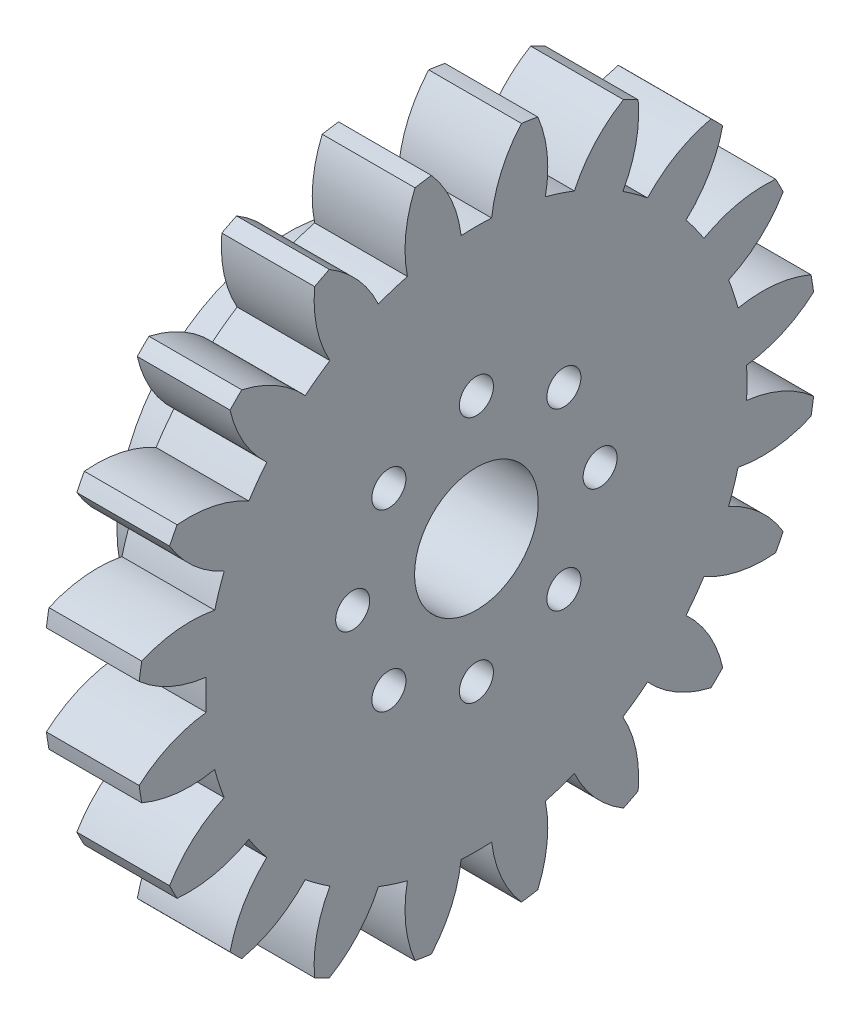
SolidWorks part; units mm, degrees
ref_plane "Plane1" through (0, 0, 0) normal (0, 0, 1) x (1, 0, 0)
ref_plane "Plane2" through (0, 0, 0) normal (0, 1, 0) x (1, 0, 0)
ref_plane "Plane3" through (0, 0, 0) normal (1, 0, 0) x (0, 0, -1)
other "Configuration Table"
sketch "HoldingSke" plane through (0, 0, 0) normal (0, 1, 0) x (1, 0, 0)
  line L0 (0, 0) -> (0.4698, -0.171)
  line L1 (-15, 0) -> (100, 0) construction
  line L2 (0, 0) -> (-2.1039, 2.3779)
  line L3 (0, 0) -> (-11.863, 4.5341)
  line L4 (0, 0) -> (8.1152, 2.9537)
  line L5 (0, 0) -> (-11.4777, -4.2808)
  line L6 (0, 0) -> (-4.9738, -3.3558)
  line L7 (-2.1039, 2.3779) -> (0.5329, 14.3408)
  line L8 (-76.2, 54.61) -> (-74.8, 54.61)
  line L9 (-71.009, 38.7566) -> (-53.1078, 45.2721)
  line L10 (-76.2, 71.12) -> (104.1128, 71.12)
  line L11 (0, 0) -> (-6, 0)
  line L12 (-76.2, 101.6) -> (-76.133, 101.6)
  line L13 (24.9733, 27.94) -> (52.9518, 28.4284)
  line L14 (24.9733, 27.94) -> (24.9743, 27.94)
  line L15 (24.9733, 27.94) -> (100.4006, 29.5858)
  line L16 (-63.627, -2) -> (-12.827, -2)
  circle A0 centre (0, 0) radius 4
  circle A1 centre (0, 0) radius 11
  circle A2 centre (0, 0) radius 11
  circle A3 centre (0, 0) radius 4
  dimension "MHD" = 22
  dimension "Hub_dia" = 22
  dimension "Bore" = 8
  dimension "MBD" = 8
  dimension "Num_teeth" = 20
  dimension "Pitch" = 0.5
  dimension "Overall_len" = 12.25
  dimension "Show_teeth" = 20
  dimension "Thickness" = 6
  dimension "OAL" = 12.2501
  dimension "T_dim" = 1.4
  dimension "Ap" = 20
  dimension "H" = 19.05
  dimension "Pitch_radius" = 180.3128
  dimension "Width" = 6
  dimension "Backlash" = 0.067
  dimension "Addendum_fac" = 1
  dimension "Dedendum_fac" = 1.25
  dimension "Clearance_fac" = 0.25
  dimension "Dedendum_add" = 0.001
  dimension "Module" = 2
sketch "BasProSke" plane through (0, 0, 0) normal (0, 1, 0) x (1, 0, 0)
  line L0 (-10, 0) -> (60, 0) construction
  line L1 (0, 0) -> (0, 22)
  line L2 (0, 0) -> (6, 0)
  line L3 (6, 0) -> (6, 22)
  line L4 (6, 22) -> (0, 22)
  dimension "Thickness" = 6
  dimension "Diameter" = 44
revolve "Base-Revolve" add sketch "BasProSke" angle 360 about L0
sketch "TooCutSke" plane through (0, 0, 0) normal (1, 0, 0) x (0, 0, -1)
  line L1 (0, 0) -> (0, 107) construction
  line L2 (0, 0) -> (-1.6864, 19.9288) construction
  line L3 (0, 0) -> (-6.2409, 39.4033) construction
  line L4 (-1.6864, 19.9288) -> (-3.1204, 19.7016) construction
  arc A0 (0.9862, 17.4712) -> (-0.9862, 17.4712) centre (0, 0) ccw
  arc A1 (2.9329, 21.8293) -> (-2.9329, 21.8293) centre (0, 0) ccw
  circle A2 centre (0, 0) radius 20 construction
  circle A3 centre (0, 0) radius 18.7939 construction
  arc A4 (-0.9862, 17.4712) -> (-2.9329, 21.8293) centre (-8.9313, 16.536) ccw
  arc A5 (2.9329, 21.8293) -> (0.9862, 17.4712) centre (8.9313, 16.536) ccw
  dimension "Root_dia" = 34.998
  dimension "Overcut_dia" = 44.0508
  dimension "Pitch_dia" = 40
  dimension "Base_dia" = 37.5877
  dimension "Flank_rad" = 8
  dimension "Half_ang" = 9
  dimension "Half_CT" = 1.4519
extrude "ToothCut" cut sketch "TooCutSke" along normal through all
fillet "Breaks" [suppressed] radius 0.04
fillet "RootFillets" [suppressed] radius 0.501
pattern_circular "TeethCuts" count 20 every 18 about axis through (-10, 0, 0) along (1, 0, 0) of "ToothCut", "RootFillets", "Breaks"
sketch "HubNeaOneSke" plane through (0, 0, 0) normal (-1, 0, 0) x (0, 0, 1)
  circle A0 centre (0, 0) radius 11
  dimension "Diameter" = 22
extrude "HubNearOne" add sketch "HubNeaOneSke" along normal blind 6.2501
sketch "HubNeaBotSke" plane through (0, 0, 0) normal (-1, 0, 0) x (0, 0, 1)
  circle A0 centre (0, 0) radius 11
  dimension "Diameter" = 22
extrude "HubNearBoth" [suppressed] add sketch "HubNeaBotSke" along normal blind 3.125
ref_plane "FarPln" through (6, 0, 0) normal (1, 0, 0) x (0, 0, -1)
sketch "HubFarSke" plane through (6, 0, 0) normal (1, 0, 0) x (0, 0, -1)
  circle A0 centre (0, 0) radius 11
  dimension "Diameter" = 22
extrude "HubFar" [suppressed] add sketch "HubFarSke" along normal blind 3.125
sketch "BorSke" plane through (0, 0, 0) normal (1, 0, 0) x (0, 0, -1)
  circle A0 centre (0, 0) radius 4
  dimension "Diameter" = 8
extrude "Bore" cut sketch "BorSke" along normal mid plane 24.5001
sketch "KeySke" plane through (0, 0, 0) normal (1, 0, 0) x (0, 0, -1)
  line L0 (-1.5, 0) -> (-1.5, 5.4)
  line L1 (-1.5, 5.4) -> (1.5, 5.4)
  line L2 (1.5, 5.4) -> (1.5, 0)
  line L3 (0, 0) -> (0, 34) construction
  line L4 (-1.5, 0) -> (1.5, 0)
  dimension "Offset" = 5.4
  dimension "Width" = 3
extrude "Keyway" [suppressed] cut sketch "KeySke" along normal mid plane 24.5001
pattern_circular "Keyway2" [suppressed] count 2 every 90 about axis through (-10, 0, 0) along (1, 0, 0)
hole_wizard "M2 Clearance Hole1" positions "Sketch1" profile "Sketch2" hole size "M2" standard "ANSI Metric" end condition through all
sketch "Sketch1" plane through (6, 0, 0) normal (1, 0, 0) x (0, 0, -1)
  circle A0 centre (0, 0) radius 8
  circle A1 centre (0, 0) radius 8
  circle A2 centre (0, 0) radius 8
  circle A3 centre (0, 0) radius 8
  circle A4 centre (0, 0) radius 8
  circle A5 centre (0, 0) radius 8
  circle A6 centre (0, 0) radius 8
  circle A7 centre (0, 0) radius 8
  point P2 (0, 8)
  point P23 (0, 8)
  point P32 (5.6569, 5.6569)
  point P34 (8, 0)
  point P36 (5.6569, -5.6569)
  point P38 (0, -8)
  point P40 (-5.6569, -5.6569)
  point P42 (-8, 0)
  point P44 (-5.6569, 5.6569)
  dimension "D1" = 16
  dimension "D2" = 8
sketch "Sketch2" plane through (6, 8, 0) normal (0, 1, 0) x (0, 0, -1)
  line L0 (0, 0) -> (0, 12.2501)
  line L1 (0, 12.2501) -> (1.1, 12.2501)
  line L2 (1.1, 12.2501) -> (1.1, 0)
  line L5 (1.1, 0) -> (0, 0)
  line L11 (0, -6.35) -> (0, 107.95) construction
  dimension "Thru Hole Dia." = 2.2
  dimension "Thru Hole Depth" = 12.2501
equation "' \"Module@HoldingSke\" = 6.35"
equation "' \"Num_teeth@HoldingSke\" = 12"
equation "' \"Ap@HoldingSke\" =  20"
equation "' \"Ap@HoldingSke\" = 20"
equation "' \"Width@HoldingSke\" = 0.5 * 25.4"
equation "' \"Hub_dia@HoldingSke\"= 1 * 25.4"
equation "' \"Hub_dia@HoldingSke\" = 1 * 25.4"
equation "' \"Overall_len@HoldingSke\" = 1.0 * 25.4"
equation "' \"Bore@HoldingSke\" = 0.75 * 25.4"
equation "' \"T_dim@HoldingSke\" = 0.1 * 25.4"
equation "' \"Width@KeySke\" = 0.25 * 25.4"
equation "' \"Show_teeth@HoldingSke\" = 13"
equation "' \"Backlash@HoldingSke\" = 0.009 * 25.4"
equation "' \"Addendum_fac@HoldingSke\" = 1.0"
equation "' \"Dedendum_fac@HoldingSke\" = 1.25"
equation "' \"Dedendum_add@HoldingSke\" = 0.00005 * 25.4"
equation "' \"Clearance_fac@HoldingSke\" = 0.25"
equation "\"Pitch@HoldingSke\" = 1 / \"Module@HoldingSke\""
equation "\"Overcut_dia@TooCutSke\" = (\"Num_teeth@HoldingSke\" + 2 * \"Addendum_fac@HoldingSke\") / \"Pitch@HoldingSke\" + 0.002 * 25.4"
equation "\"Pitch_dia@TooCutSke\" = \"Num_teeth@HoldingSke\" / \"Pitch@HoldingSke\""
equation "\"Base_dia@TooCutSke\" = \"Num_teeth@HoldingSke\" / \"Pitch@HoldingSke\" * cos((\"Ap@HoldingSke\"  * 3.14159265 / 180))"
equation "\"Root_dia@TooCutSke\" = (\"Num_teeth@HoldingSke\" + 2) / \"Pitch@HoldingSke\" - 2 * (\"Addendum_fac@HoldingSke\" + \"Dedendum_fac@HoldingSke\") / \"Pitch@HoldingSke\" - \"Dedendum_add@HoldingSke\" * 2"
equation "\"Half_ang@TooCutSke\" = 180 / \"Num_teeth@HoldingSke\""
equation "\"Half_CT@TooCutSke\" = \"Num_teeth@HoldingSke\" / \"Pitch@HoldingSke\" * sin((3.14159265 / 2 / \"Num_teeth@HoldingSke\")) / 2 - 7 * \"Backlash@HoldingSke\" / 4"
equation "\"Flank_rad@TooCutSke\" = \"Num_teeth@HoldingSke\" / \"Pitch@HoldingSke\" / 5"
equation "\"Radius@RootFillets\" = \"Clearance_fac@HoldingSke\" / \"Pitch@HoldingSke\" + \"Dedendum_add@HoldingSke\""
equation "\"Break_rad@Breaks\" = 0.02 / \"Pitch@HoldingSke\""
equation "\"Thickness@HoldingSke\" = \"Width@HoldingSke\""
equation "\"OAL@HoldingSke\" = \"Thickness@HoldingSke\""
equation "\"MHD@HoldingSke\" = (\"Num_teeth@HoldingSke\" + 2) / \"Pitch@HoldingSke\" - 2 * (\"Addendum_fac@HoldingSke\" + \"Dedendum_fac@HoldingSke\")  / \"Pitch@HoldingSke\" - \"Dedendum_add@HoldingSke\" * 2"
equation "\"MBD@HoldingSke\" = (\"Num_teeth@HoldingSke\" + 2) / \"Pitch@HoldingSke\" - 2 * (\"Addendum_fac@HoldingSke\" + \"Dedendum_fac@HoldingSke\")  / \"Pitch@HoldingSke\" - \"Dedendum_add@HoldingSke\" * 2 - 0.002 * 25.4"
equation "\"MHD@HoldingSke\" = ((sgn( \"MHD@HoldingSke\" - \"Hub_dia@HoldingSke\" )-1)*( \"MHD@HoldingSke\" - \"Hub_dia@HoldingSke\" ))/-2+ \"Hub_dia@HoldingSke\""
equation "\"MBD@HoldingSke\" = ((sgn( \"MBD@HoldingSke\" - \"Bore@HoldingSke\" )-1)*( \"MBD@HoldingSke\" - \"Bore@HoldingSke\" ))/-2+ \"Bore@HoldingSke\""
equation "\"OAL@HoldingSke\" = ((sgn( \"OAL@HoldingSke\" - \"Overall_len@HoldingSke\" )+1)*( \"OAL@HoldingSke\" - \"Overall_len@HoldingSke\" ))/2 + \"Overall_len@HoldingSke\" + 0.000002 * 25.4"
equation "\"Num_teeth@TeethCuts\" = int( \"Show_teeth@HoldingSke\" ) + 1"
equation "\"Num_teeth@TeethCuts\" = ((sgn( \"Num_teeth@TeethCuts\" - \"Num_teeth@HoldingSke\" )-1)*( \"Num_teeth@TeethCuts\" - \"Num_teeth@HoldingSke\" ))/-2+ \"Num_teeth@HoldingSke\""
equation "\"Num_teeth@TeethCuts\" = ((sgn( \"Num_teeth@TeethCuts\" - 2.0)+1)*( \"Num_teeth@TeethCuts\" - 2.0))/2 +2.0"
equation "\"Angle@TeethCuts\" = 360.0 / \"Num_teeth@HoldingSke\""
equation "\"Diameter@BasProSke\" = (\"Num_teeth@HoldingSke\" + 2 * \"Addendum_fac@HoldingSke\") / \"Pitch@HoldingSke\""
equation "\"Thickness@BasProSke\"  = \"Thickness@HoldingSke\""
equation "' \"Fillet_rad@BasProSke\" =  \"Thickness@HoldingSke\" * 0.05"
equation "' \"Fillet_rad@BasProSke\" = \"Thickness@HoldingSke\" * 0.05"
equation "\"MHD@HoldingSke\" = ((sgn( \"MHD@HoldingSke\" - \"Root_dia@TooCutSke\" )-1)*( \"MHD@HoldingSke\" - \"Root_dia@TooCutSke\" ))/-2+ \"Root_dia@TooCutSke\""
equation "\"Diameter@HubNeaOneSke\" = \"MHD@HoldingSke\""
equation "\"Length@HubNearOne\" = \"OAL@HoldingSke\" - \"Thickness@BasProSke\""
equation "\"Diameter@HubNeaBotSke\" = \"MHD@HoldingSke\""
equation "\"Length@HubNearBoth\" = ( \"OAL@HoldingSke\" - \"Thickness@BasProSke\" ) / 2.0"
equation "\"Thickness@FarPln\" = \"Thickness@BasProSke\""
equation "\"Diameter@HubFarSke\" = \"MHD@HoldingSke\""
equation "\"Length@HubFar\" = ( \"OAL@HoldingSke\" - \"Thickness@BasProSke\" ) / 2.0"
equation "\"Diameter@BorSke\" = \"MBD@HoldingSke\""
equation "\"D1@Bore\" = \"OAL@HoldingSke\" * 2.0"
equation "\"D1@Keyway\" = \"OAL@HoldingSke\" * 2.0"
equation "\"Offset@KeySke\" = \"T_dim@HoldingSke\" + \"MBD@HoldingSke\" / 2.0"
